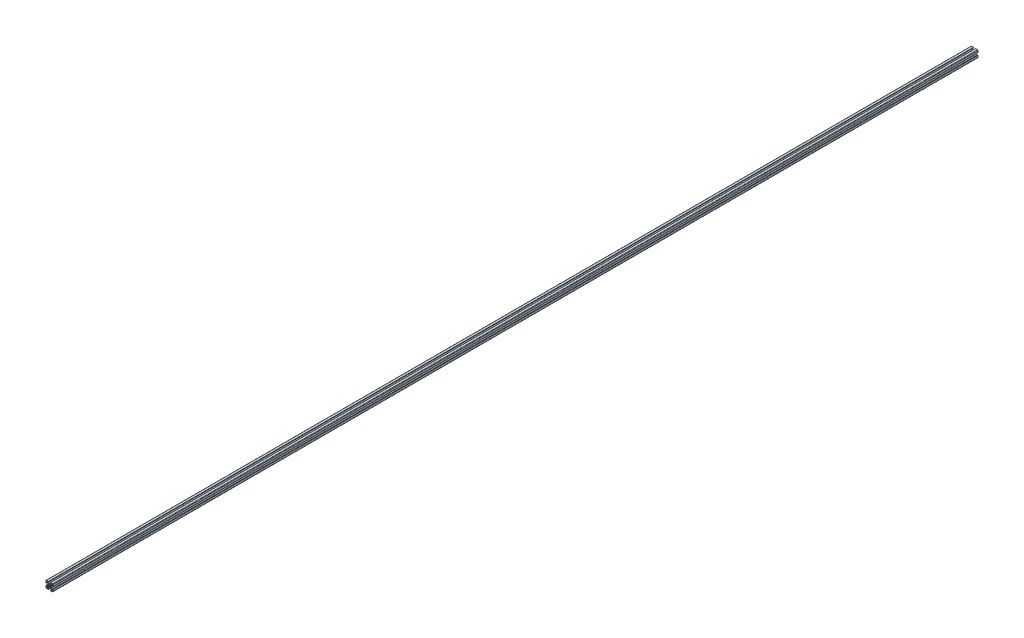
SolidWorks part; units mm, degrees
material "6105-T5 Aluminum"
ref_plane "Front Plane" through (0, 0, 0) normal (0, 0, 1) x (1, 0, 0)
ref_plane "Top Plane" through (0, 0, 0) normal (0, 1, 0) x (1, 0, 0)
ref_plane "Right Plane" through (0, 0, 0) normal (1, 0, 0) x (0, 0, -1)
sketch "Sketch1" plane through (0, 0, 0) normal (0, 0, 1) x (1, 0, 0)
  line L0 (9.5, -13.3189) -> (9.5, -9.88)
  line L1 (9.88, -9.5) -> (13.3189, -9.5)
  line L2 (13.6999, -9.881) -> (13.6999, -12.6999)
  line L3 (12.6999, -13.6999) -> (9.881, -13.6999)
  line L4 (-13.3189, -9.5) -> (-9.88, -9.5)
  line L5 (-9.5, -9.88) -> (-9.5, -13.3189)
  line L6 (-9.881, -13.6999) -> (-12.6999, -13.6999)
  line L7 (-13.6999, -12.6999) -> (-13.6999, -9.881)
  line L8 (-1.4942, -3.1981) -> (-2.4733, -3.9799)
  line L9 (-3.9799, -2.4733) -> (-3.1981, -1.4942)
  line L10 (-3.1981, 1.4942) -> (-3.9799, 2.4733)
  line L11 (-2.4733, 3.9799) -> (-1.4942, 3.1981)
  line L12 (1.4942, 3.1981) -> (2.4733, 3.9799)
  line L13 (3.9799, 2.4733) -> (3.1981, 1.4942)
  line L14 (3.1981, -1.4942) -> (3.9799, -2.4733)
  line L15 (2.4733, -3.9799) -> (1.4942, -3.1981)
  line L16 (-9.5, 13.3189) -> (-9.5, 9.88)
  line L17 (-9.88, 9.5) -> (-13.3189, 9.5)
  line L18 (-13.6999, 9.881) -> (-13.6999, 12.6999)
  line L19 (-12.6999, 13.6999) -> (-9.881, 13.6999)
  line L20 (9.881, 13.6999) -> (12.6999, 13.6999)
  line L21 (13.6999, 12.6999) -> (13.6999, 9.881)
  line L22 (13.3189, 9.5) -> (9.88, 9.5)
  line L23 (9.5, 9.88) -> (9.5, 13.3189)
  line L24 (12.7425, -4.5) -> (12.7425, -7.7325)
  line L25 (12.2428, -8.25) -> (10.2602, -8.25)
  line L26 (9.9066, -8.1035) -> (5.9811, -4.178)
  line L27 (5.8347, -3.8245) -> (5.8347, -1.0125)
  line L28 (5.8347, -1.0125) -> (5.3247, -0.0625)
  line L29 (5.3247, -0.0625) -> (5.8347, 0.8875)
  line L30 (5.8347, 0.8875) -> (5.8347, 3.8245)
  line L31 (5.9811, 4.178) -> (9.9066, 8.1035)
  line L32 (10.2602, 8.25) -> (12.2428, 8.25)
  line L33 (12.7425, 7.7325) -> (12.7425, 4.5)
  line L34 (13.2425, 4) -> (14.4999, 4)
  line L35 (14.9999, 4.5) -> (14.9999, 12.9999)
  line L36 (12.9999, 14.9999) -> (4.5, 14.9999)
  line L37 (4, 14.4999) -> (4, 13.2425)
  line L38 (4.5, 12.7425) -> (7.7325, 12.7425)
  line L39 (8.25, 12.2428) -> (8.25, 10.2602)
  line L40 (8.1035, 9.9066) -> (4.178, 5.9811)
  line L41 (3.8245, 5.8347) -> (0.95, 5.8347)
  line L42 (0.95, 5.8347) -> (0, 5.3247)
  line L43 (0, 5.3247) -> (-0.95, 5.8347)
  line L44 (-0.95, 5.8347) -> (-3.8245, 5.8347)
  line L45 (-4.178, 5.9811) -> (-8.1035, 9.9066)
  line L46 (-8.25, 10.2602) -> (-8.25, 12.2428)
  line L47 (-7.7325, 12.7425) -> (-4.5, 12.7425)
  line L48 (-4, 13.2425) -> (-4, 14.4999)
  line L49 (-4.5, 14.9999) -> (-12.9999, 14.9999)
  line L50 (-14.9999, 12.9999) -> (-14.9999, 4.5)
  line L51 (-14.4999, 4) -> (-13.2425, 4)
  line L52 (-12.7425, 4.5) -> (-12.7425, 7.7325)
  line L53 (-12.2428, 8.25) -> (-10.2602, 8.25)
  line L54 (-9.9066, 8.1035) -> (-5.9811, 4.178)
  line L55 (-5.8347, 3.8245) -> (-5.8347, 0.8875)
  line L56 (-5.8347, 0.8875) -> (-5.3247, -0.0625)
  line L57 (-5.3247, -0.0625) -> (-5.8347, -1.0125)
  line L58 (-5.8347, -1.0125) -> (-5.8347, -3.8245)
  line L59 (-5.9811, -4.178) -> (-9.9066, -8.1035)
  line L60 (-10.2602, -8.25) -> (-12.2428, -8.25)
  line L61 (-12.7425, -7.7325) -> (-12.7425, -4.5)
  line L62 (-13.2425, -4) -> (-14.4999, -4)
  line L63 (-14.9999, -4.5) -> (-14.9999, -12.9999)
  line L64 (-12.9999, -14.9999) -> (-4.5, -14.9999)
  line L65 (-4, -14.4999) -> (-4, -13.2425)
  line L66 (-4.5, -12.7425) -> (-7.7325, -12.7425)
  line L67 (-8.25, -12.2428) -> (-8.25, -10.2602)
  line L68 (-8.1035, -9.9066) -> (-4.178, -5.9811)
  line L69 (-3.8245, -5.8347) -> (-0.95, -5.8347)
  line L70 (-0.95, -5.8347) -> (0, -5.3247)
  line L71 (0, -5.3247) -> (0.95, -5.8347)
  line L72 (0.95, -5.8347) -> (3.8245, -5.8347)
  line L73 (4.178, -5.9811) -> (8.1035, -9.9066)
  line L74 (8.25, -10.2602) -> (8.25, -12.2428)
  line L75 (7.7325, -12.7425) -> (4.5, -12.7425)
  line L76 (4, -13.2425) -> (4, -14.4999)
  line L77 (4.5, -14.9999) -> (12.9999, -14.9999)
  line L78 (14.9999, -12.9999) -> (14.9999, -4.5)
  line L79 (14.4999, -4) -> (13.2425, -4)
  arc A0 (9.5, -13.3189) -> (9.881, -13.6999) centre (9.881, -13.3189) ccw
  arc A1 (9.88, -9.5) -> (9.5, -9.88) centre (9.88, -9.88) ccw
  arc A2 (13.6999, -9.881) -> (13.3189, -9.5) centre (13.3189, -9.881) ccw
  arc A3 (12.6999, -13.6999) -> (13.6999, -12.6999) centre (12.6999, -12.6999) ccw
  arc A4 (-13.3189, -9.5) -> (-13.6999, -9.881) centre (-13.3189, -9.881) ccw
  arc A5 (-9.5, -9.88) -> (-9.88, -9.5) centre (-9.88, -9.88) ccw
  arc A6 (-9.881, -13.6999) -> (-9.5, -13.3189) centre (-9.881, -13.3189) ccw
  arc A7 (-13.6999, -12.6999) -> (-12.6999, -13.6999) centre (-12.6999, -12.6999) ccw
  arc A8 (-1.4942, -3.1981) -> (1.4942, -3.1981) centre (0, 0) ccw
  arc A9 (-3.9799, -2.4733) -> (-2.4733, -3.9799) centre (-3.1422, -3.1422) ccw
  arc A10 (-3.1981, 1.4942) -> (-3.1981, -1.4942) centre (0, 0) ccw
  arc A11 (-2.4733, 3.9799) -> (-3.9799, 2.4733) centre (-3.1422, 3.1422) ccw
  arc A12 (1.4942, 3.1981) -> (-1.4942, 3.1981) centre (0, 0) ccw
  arc A13 (3.9799, 2.4733) -> (2.4733, 3.9799) centre (3.1422, 3.1422) ccw
  arc A14 (3.1981, -1.4942) -> (3.1981, 1.4942) centre (0, 0) ccw
  arc A15 (2.4733, -3.9799) -> (3.9799, -2.4733) centre (3.1422, -3.1422) ccw
  arc A16 (-9.5, 13.3189) -> (-9.881, 13.6999) centre (-9.881, 13.3189) ccw
  arc A17 (-9.88, 9.5) -> (-9.5, 9.88) centre (-9.88, 9.88) ccw
  arc A18 (-13.6999, 9.881) -> (-13.3189, 9.5) centre (-13.3189, 9.881) ccw
  arc A19 (-12.6999, 13.6999) -> (-13.6999, 12.6999) centre (-12.6999, 12.6999) ccw
  arc A20 (9.881, 13.6999) -> (9.5, 13.3189) centre (9.881, 13.3189) ccw
  arc A21 (13.6999, 12.6999) -> (12.6999, 13.6999) centre (12.6999, 12.6999) ccw
  arc A22 (13.3189, 9.5) -> (13.6999, 9.881) centre (13.3189, 9.881) ccw
  arc A23 (9.5, 9.88) -> (9.88, 9.5) centre (9.88, 9.88) ccw
  arc A24 (13.2425, -4) -> (12.7425, -4.5) centre (13.2425, -4.5) ccw
  arc A25 (12.2428, -8.25) -> (12.7425, -7.7325) centre (12.2428, -7.75) ccw
  arc A26 (9.9066, -8.1035) -> (10.2602, -8.25) centre (10.2602, -7.75) ccw
  arc A27 (5.8347, -3.8245) -> (5.9811, -4.178) centre (6.3347, -3.8245) ccw
  arc A28 (5.9811, 4.178) -> (5.8347, 3.8245) centre (6.3347, 3.8245) ccw
  arc A29 (10.2602, 8.25) -> (9.9066, 8.1035) centre (10.2602, 7.75) ccw
  arc A30 (12.7425, 7.7325) -> (12.2428, 8.25) centre (12.2428, 7.75) ccw
  arc A31 (12.7425, 4.5) -> (13.2425, 4) centre (13.2425, 4.5) ccw
  arc A32 (14.4999, 4) -> (14.9999, 4.5) centre (14.4999, 4.5) ccw
  arc A33 (14.9999, 12.9999) -> (12.9999, 14.9999) centre (12.9999, 12.9999) ccw
  arc A34 (4.5, 14.9999) -> (4, 14.4999) centre (4.5, 14.4999) ccw
  arc A35 (4, 13.2425) -> (4.5, 12.7425) centre (4.5, 13.2425) ccw
  arc A36 (8.25, 12.2428) -> (7.7325, 12.7425) centre (7.75, 12.2428) ccw
  arc A37 (8.1035, 9.9066) -> (8.25, 10.2602) centre (7.75, 10.2602) ccw
  arc A38 (3.8245, 5.8347) -> (4.178, 5.9811) centre (3.8245, 6.3347) ccw
  arc A39 (-4.178, 5.9811) -> (-3.8245, 5.8347) centre (-3.8245, 6.3347) ccw
  arc A40 (-8.25, 10.2602) -> (-8.1035, 9.9066) centre (-7.75, 10.2602) ccw
  arc A41 (-7.7325, 12.7425) -> (-8.25, 12.2428) centre (-7.75, 12.2428) ccw
  arc A42 (-4.5, 12.7425) -> (-4, 13.2425) centre (-4.5, 13.2425) ccw
  arc A43 (-4, 14.4999) -> (-4.5, 14.9999) centre (-4.5, 14.4999) ccw
  arc A44 (-12.9999, 14.9999) -> (-14.9999, 12.9999) centre (-12.9999, 12.9999) ccw
  arc A45 (-14.9999, 4.5) -> (-14.4999, 4) centre (-14.4999, 4.5) ccw
  arc A46 (-13.2425, 4) -> (-12.7425, 4.5) centre (-13.2425, 4.5) ccw
  arc A47 (-12.2428, 8.25) -> (-12.7425, 7.7325) centre (-12.2428, 7.75) ccw
  arc A48 (-9.9066, 8.1035) -> (-10.2602, 8.25) centre (-10.2602, 7.75) ccw
  arc A49 (-5.8347, 3.8245) -> (-5.9811, 4.178) centre (-6.3347, 3.8245) ccw
  arc A50 (-5.9811, -4.178) -> (-5.8347, -3.8245) centre (-6.3347, -3.8245) ccw
  arc A51 (-10.2602, -8.25) -> (-9.9066, -8.1035) centre (-10.2602, -7.75) ccw
  arc A52 (-12.7425, -7.7325) -> (-12.2428, -8.25) centre (-12.2428, -7.75) ccw
  arc A53 (-12.7425, -4.5) -> (-13.2425, -4) centre (-13.2425, -4.5) ccw
  arc A54 (-14.4999, -4) -> (-14.9999, -4.5) centre (-14.4999, -4.5) ccw
  arc A55 (-14.9999, -12.9999) -> (-12.9999, -14.9999) centre (-12.9999, -12.9999) ccw
  arc A56 (-4.5, -14.9999) -> (-4, -14.4999) centre (-4.5, -14.4999) ccw
  arc A57 (-4, -13.2425) -> (-4.5, -12.7425) centre (-4.5, -13.2425) ccw
  arc A58 (-8.25, -12.2428) -> (-7.7325, -12.7425) centre (-7.75, -12.2428) ccw
  arc A59 (-8.1035, -9.9066) -> (-8.25, -10.2602) centre (-7.75, -10.2602) ccw
  arc A60 (-3.8245, -5.8347) -> (-4.178, -5.9811) centre (-3.8245, -6.3347) ccw
  arc A61 (4.178, -5.9811) -> (3.8245, -5.8347) centre (3.8245, -6.3347) ccw
  arc A62 (8.25, -10.2602) -> (8.1035, -9.9066) centre (7.75, -10.2602) ccw
  arc A63 (7.7325, -12.7425) -> (8.25, -12.2428) centre (7.75, -12.2428) ccw
  arc A64 (4.5, -12.7425) -> (4, -13.2425) centre (4.5, -13.2425) ccw
  arc A65 (4, -14.4999) -> (4.5, -14.9999) centre (4.5, -14.4999) ccw
  arc A66 (12.9999, -14.9999) -> (14.9999, -12.9999) centre (12.9999, -12.9999) ccw
  arc A67 (14.9999, -4.5) -> (14.4999, -4) centre (14.4999, -4.5) ccw
extrude "Extrude1" add sketch "Sketch1" against normal blind 4000
